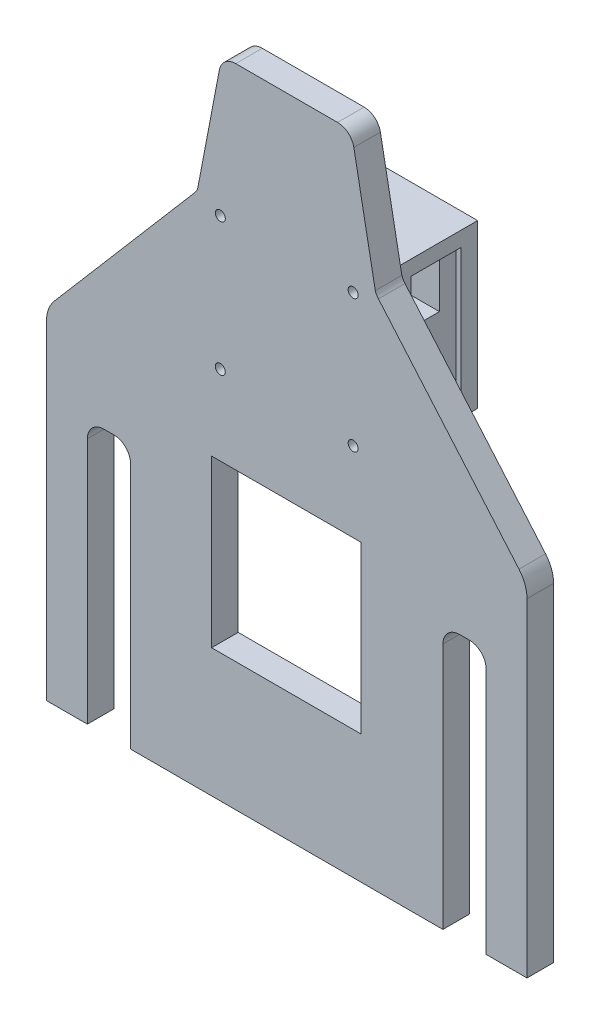
SolidWorks part; units mm, degrees
ref_plane "Front Plane" through (0, 0, 0) normal (0, 0, 1) x (1, 0, 0)
ref_plane "Top Plane" through (0, 0, 0) normal (0, 1, 0) x (1, 0, 0)
ref_plane "Right Plane" through (0, 0, 0) normal (1, 0, 0) x (0, 0, -1)
sketch "Sketch1" plane through (0, 0, 0) normal (0, 0, 1) x (1, 0, 0)
  line L4 (70, 309.9858) -> (85.2992, 309.9858)
  line L6 (43.2101, 271.7903) -> (49.7246, 305.9232)
  line L7 (42.2614, 270.1156) -> (0.0495, 220.7861)
  line L8 (0.0495, 220.7861) -> (42.9, 220.7861) construction
  line L9 (42.9, 220.7861) -> (42.9, 270.8599) construction
  line L10 (96.9829, 220.8599) -> (96.9829, 270.8599) construction
  line L11 (112.4871, 25.7747) -> (89.3829, 25.7747) construction
  line L12 (27.5129, 25.7747) -> (50.5, 25.7747) construction
  line L13 (25.2828, 25.7823) -> (2.6386, 25.8599)
  line L14 (96.6727, 271.7903) -> (90.212, 305.9159)
  line L15 (70, 329.5221) -> (70, -78.2612) construction
  line L18 (50.5, 25.7747) -> (50.5, 0) construction
  line L19 (70, 309.9858) -> (54.636, 309.9858)
  line L20 (135.9829, 220.8599) -> (96.9829, 220.8599) construction
  line L21 (139.9505, 220.7861) -> (135.9829, 220.8599) construction
  line L25 (89.3829, 25.7747) -> (89.3829, 0) construction
  line L27 (89.3829, 0) -> (50.5, 0)
  line L28 (15.2188, 54.8072) -> (17.7021, 54.8072)
  line L35 (125.0395, 54.8072) -> (122.0396, 54.8072)
  line L36 (122.0396, 194.8072) -> (125.0395, 194.8072)
  line L37 (117.0396, 59.8072) -> (117.0396, 189.8072)
  line L38 (130.0395, 189.8072) -> (130.0395, 59.8072)
  line L39 (142.3614, 214.274) -> (142.3614, 30.8599)
  line L40 (97.6215, 270.1156) -> (139.9505, 220.7861)
  line L41 (-2.3614, 214.274) -> (-2.3614, 30.8599)
  line L42 (9.9605, 189.8072) -> (9.9605, 60.0656)
  line L43 (22.9604, 60.0656) -> (22.9604, 189.8072)
  line L44 (17.9604, 194.8072) -> (14.9605, 194.8072)
  line L45 (28.9972, 24.1103) -> (50.5, 0)
  line L46 (114.7172, 25.7823) -> (137.3614, 25.8599)
  line L47 (89.3829, 0) -> (111.0028, 24.1103)
  arc A1 (42.2614, 270.1156) -> (43.2101, 271.7903) centre (38.4667, 273.3715) ccw
  arc A5 (97.6215, 270.1156) -> (96.6727, 271.7903) centre (101.4161, 273.3715) cw
  arc A8 (137.3614, 25.8599) -> (142.3614, 30.8599) centre (137.3614, 30.8599) ccw
  arc A9 (2.6386, 25.8599) -> (-2.3614, 30.8599) centre (2.6386, 30.8599) cw
  arc A10 (49.7246, 305.9232) -> (54.636, 309.9858) centre (54.636, 304.9858) cw
  arc A11 (85.2992, 309.9858) -> (90.212, 305.9159) centre (85.2992, 304.9858) cw
  arc A12 (139.9505, 220.7861) -> (142.3614, 214.274) centre (132.3614, 214.274) cw
  arc A13 (0.0495, 220.7861) -> (-2.3614, 214.274) centre (7.6386, 214.274) ccw
  arc A14 (25.2828, 25.7823) -> (28.9972, 24.1103) centre (25.2657, 20.7823) cw
  arc A15 (114.7172, 25.7823) -> (111.0028, 24.1103) centre (114.7343, 20.7823) ccw
  arc A16 (17.9604, 194.8072) -> (22.9604, 189.8072) centre (17.9604, 189.8072) cw
  arc A17 (9.9605, 189.8072) -> (14.9605, 194.8072) centre (14.9605, 189.8072) cw
  arc A18 (125.0395, 54.8072) -> (130.0395, 59.8072) centre (125.0395, 59.8072) ccw
  arc A19 (122.0396, 54.8072) -> (117.0396, 59.8072) centre (122.0396, 59.8072) cw
  arc A20 (125.0395, 194.8072) -> (130.0395, 189.8072) centre (125.0395, 189.8072) cw
  arc A21 (117.0396, 189.8072) -> (122.0396, 194.8072) centre (122.0396, 189.8072) cw
  arc A22 (17.7021, 54.8072) -> (22.9604, 60.0656) centre (17.7021, 60.0656) ccw
  arc A23 (15.2188, 54.8072) -> (9.9605, 60.0656) centre (15.2188, 60.0656) cw
  point P18 (22.9604, 194.8072)
  point P51 (9.9605, 194.8072)
  point P57 (130.0395, 54.8072)
  point P61 (117.0396, 54.8072)
  point P67 (130.0395, 194.8072)
  point P70 (117.0396, 194.8072)
  point P73 (0, 0)
  point P77 (22.9604, 54.8072)
  point P80 (9.9605, 54.8072)
  dimension "D1" = 5
  dimension "D2" = 5
  dimension "D3" = 5
  dimension "D4" = 10
  dimension "D5" = 5
  dimension "D6" = 5
  dimension "D7" = 5.2583
extrude "Boss-Extrude1" add sketch "Sketch1" along normal blind 8
sketch "Sketch2" plane through (0, 0, 8) normal (0, 0, 1) x (1, 0, 0)
  line L2 (92.3829, 204.0089) -> (47.3829, 204.0089)
  line L8 (47.3829, 204.0089) -> (47.3829, 154.0089)
  line L9 (47.3829, 154.0089) -> (92.3829, 154.0089)
  line L10 (92.3829, 204.0089) -> (92.3829, 154.0089)
extrude "Cut-Extrude1" cut sketch "Sketch2" against normal through all contours L10 L2 L8 L9
sketch "Sketch3" plane through (0, 0, 0) normal (0, 0, -1) x (-1, 0, 0)
  line L1 (-142.3614, 115.3599) -> (2.3614, 115.3599)
  line L3 (-142.3614, 30.8599) -> (-142.3614, 214.274) construction
  line L6 (2.3614, 214.274) -> (2.3614, 30.8599) construction
split "Split1" trim tools "Sketch3" bodies to split 102 resulting bodies 104 108
ref_plane "Plane4" through (0, 115.3599, 0) normal (0, 1, 0) x (1, 0, 0)
sketch "Sketch4" plane through (0, 115.3599, 0) normal (0, -1, 0) x (-1, 0, 0)
  line L0 (-3.7995, -8) -> (-3.7995, -4)
  line L2 (2.3614, -8) -> (-9.9605, -8) construction
  circle A1 centre (-70, -4) radius 2.5
  circle A2 centre (-40, -4) radius 2.5
  circle A3 centre (-100, -4) radius 2.5
  circle A5 centre (-137.3614, -4) radius 2.5
  circle A6 centre (-3.7995, -4) radius 2.5
sketch "Sketch5" plane through (0, 115.3599, -115.3599) normal (0, -1, 0) x (1, 0, 0)
  circle A1 centre (70, 119.3599) radius 2.5
  circle A2 centre (100, 119.3599) radius 2.5
  circle A3 centre (40, 119.3599) radius 2.5
  circle A5 centre (2.6386, 119.3599) radius 2.5
  circle A6 centre (137.3614, 119.3599) radius 2.5
extrude "Cut-Extrude6" cut sketch "Sketch5" along direction (0, -1, 0) on the side of the normal blind 5.2 contours A5 | A3 | A1
extrude "Cut-Extrude7" cut sketch "Sketch4" against normal blind 5.2
delete or keep bodies "Body-Delete/Keep 3" type delete bodies bodies 106
sketch "Sketch6" plane through (0, 0, 8) normal (0, 0, 1) x (1, 0, 0)
  circle A0 centre (50.0001, 267.9803) radius 1.5
  circle A1 centre (90.0001, 267.9803) radius 1.5
  circle A2 centre (90.0001, 227.9803) radius 1.5
  circle A3 centre (50.0001, 227.9803) radius 1.5
extrude "Cut-Extrude8" cut sketch "Sketch6" against normal through all
sketch "Sketch7" plane through (0, 0, 0) normal (0, 0, -1) x (-1, 0, 0)
  line L10 (-94.5001, 223.4803) -> (-94.5001, 272.4803)
  line L11 (-47.0001, 270.9803) -> (-47.0001, 252.9803)
  line L12 (-45.5001, 272.4803) -> (-45.5001, 223.4803)
  line L13 (-45.5001, 223.4803) -> (-94.5001, 223.4803)
  line L14 (-93.0001, 270.9803) -> (-75.0001, 270.9803)
  line L15 (-93.0001, 224.9803) -> (-75.0001, 224.9803)
  line L16 (-93.0001, 224.9803) -> (-93.0001, 242.9803)
  line L18 (-65.0001, 270.9803) -> (-65.0001, 252.9803)
  line L19 (-65.0001, 224.9803) -> (-47.0001, 224.9803)
  line L20 (-45.5001, 272.4803) -> (-94.5001, 272.4803)
  line L21 (-75.0001, 270.9803) -> (-75.0001, 252.9803)
  line L22 (-47.0001, 252.9803) -> (-65.0001, 252.9803)
  line L23 (-47.0001, 242.9803) -> (-47.0001, 224.9803)
  line L24 (-93.0001, 242.9803) -> (-75.0001, 242.9803)
  line L25 (-65.0001, 270.9803) -> (-47.0001, 270.9803)
  line L26 (-75.0001, 252.9803) -> (-93.0001, 252.9803)
  line L27 (-65.0001, 242.9803) -> (-47.0001, 242.9803)
  line L28 (-65.0001, 242.9803) -> (-65.0001, 224.9803)
  line L29 (-75.0001, 242.9803) -> (-75.0001, 224.9803)
  line L30 (-93.0001, 252.9803) -> (-93.0001, 270.9803)
extrude "Boss-Extrude2" add sketch "Sketch7" along normal blind 15
sketch "Sketch8" plane through (0, 0, -15) normal (0, 0, -1) x (-1, 0, 0)
  line L0 (-45.5001, 272.4803) -> (-94.5001, 272.4803)
  line L1 (-94.5001, 272.4803) -> (-94.5001, 223.4803)
  line L2 (-94.5001, 223.4803) -> (-45.5001, 223.4803)
  line L3 (-94.5001, 223.4803) -> (-45.5001, 223.4803) construction
  line L4 (-94.5001, 223.4803) -> (-45.5001, 223.4803) construction
  line L5 (-45.5001, 223.4803) -> (-45.5001, 272.4803)
  circle A0 centre (-50.0001, 267.9803) radius 1.5
  circle A1 centre (-90.0001, 267.9803) radius 1.5
  circle A2 centre (-50.0001, 227.9803) radius 1.5
  circle A3 centre (-90.0001, 227.9803) radius 1.5
extrude "Boss-Extrude3" add sketch "Sketch8" along normal blind 10
sketch "Sketch9" plane through (45.5001, 0, 0) normal (-1, 0, 0) x (0, 0, 1)
  line L2 (-20, 267.9803) -> (-20, 227.9803)
  line L3 (-20, 267.9803) -> (-5, 267.9803)
  line L6 (-5, 267.9803) -> (-5, 227.9803)
  line L7 (-5, 227.9803) -> (-20, 227.9803)
extrude "Cut-Extrude9" cut sketch "Sketch9" against normal blind 1.5
sketch "Sketch11" plane through (94.5001, 0, 0) normal (1, 0, 0) x (0, 0, -1)
  line L3 (20, 267.9803) -> (20, 227.9803)
  line L4 (20, 227.9803) -> (5, 227.9803)
  line L5 (5, 227.9803) -> (5, 267.9803)
  line L6 (5, 267.9803) -> (20, 267.9803)
extrude "Cut-Extrude10" cut sketch "Sketch11" against normal blind 1.5
